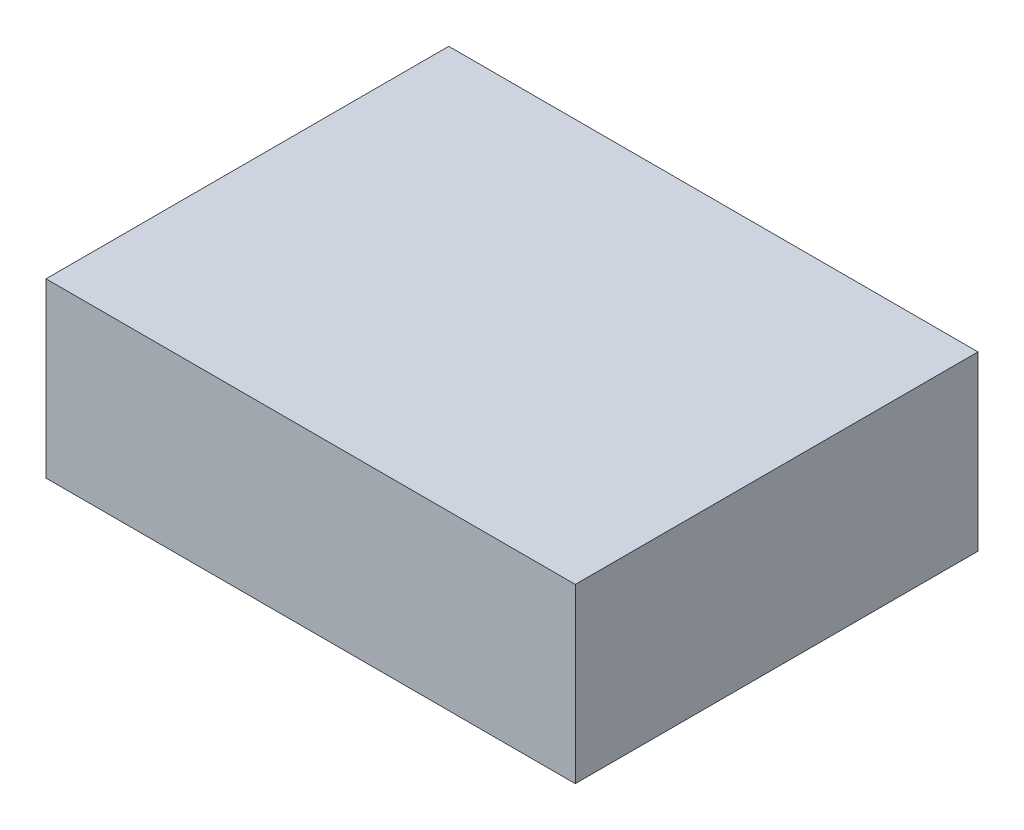
SolidWorks part; units mm, degrees
ref_plane "Plano frontal" through (0, 0, 0) normal (0, 0, 1) x (1, 0, 0)
ref_plane "Plano superior" through (0, 0, 0) normal (0, 1, 0) x (1, 0, 0)
ref_plane "Plano direito" through (0, 0, 0) normal (1, 0, 0) x (0, 0, -1)
sketch "Esboço1" plane through (0, 0, 0) normal (0, 1, 0) x (1, 0, 0)
  line L1 (-23, 17.5) -> (23, 17.5)
  line L2 (-23, 17.5) -> (-23, -17.5)
  line L3 (-23, -17.5) -> (23, -17.5)
  line L4 (23, 17.5) -> (23, -17.5)
  line L5 (-23, 17.5) -> (23, -17.5) construction
  line L6 (-23, -17.5) -> (23, 17.5) construction
  point P0 (0, 0)
  dimension "D1" = 35
  dimension "D2" = 46
extrude "Ressalto-extrusão1" add sketch "Esboço1" along normal blind 15
